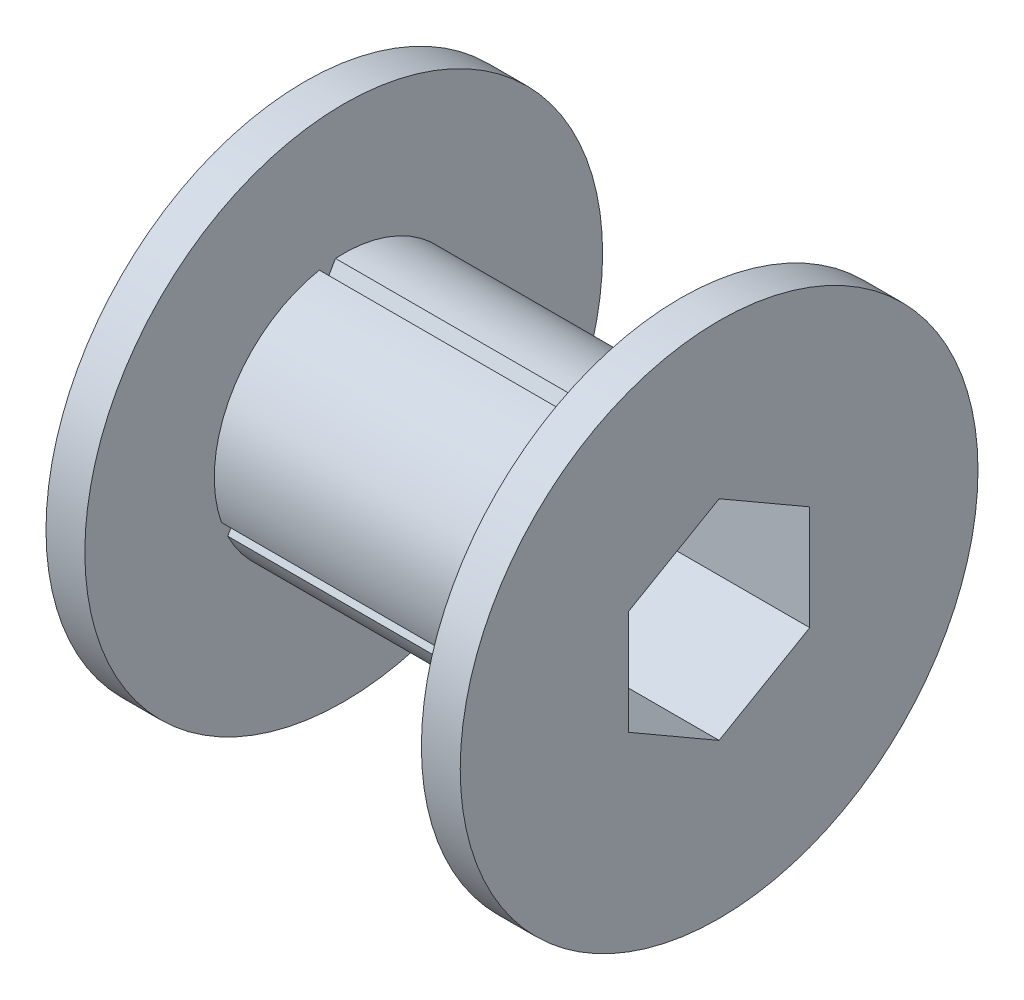
SolidWorks part; units mm, degrees
ref_plane "Front Plane" through (0, 0, 0) normal (0, 0, 1) x (1, 0, 0)
ref_plane "Top Plane" through (0, 0, 0) normal (0, 1, 0) x (1, 0, 0)
ref_plane "Right Plane" through (0, 0, 0) normal (1, 0, 0) x (0, 0, -1)
sketch "Sketch1" plane through (0, 0, 0) normal (1, 0, 0) x (0, 0, -1)
  circle A0 centre (0, 0) radius 2.5
  dimension "D1" = 5
extrude "Boss-Extrude1" add sketch "Sketch1" along normal mid plane 8
sketch "Sketch2" plane through (4, 0, 0) normal (1, 0, 0) x (0, 0, -1)
  circle A0 centre (0, 0) radius 5
  dimension "D1" = 10
extrude "Boss-Extrude2" add sketch "Sketch2" against normal blind 0.75
mirror "Mirror1" about plane through (0, 0, 0) normal (1, 0, 0) of "Boss-Extrude2"
sketch "Sketch3" plane through (0, 0, 0) normal (1, 0, 0) x (0, 0, -1)
  line L0 (1.75, 0) -> (1.75, 1.0104)
  line L1 (1.6, 0) -> (1.6, 0.9238) construction
  line L2 (1.6, -0.9238) -> (1.6, 0) construction
  line L3 (0.8, -1.3856) -> (1.6, -0.9238) construction
  line L4 (0, -1.8475) -> (0.8, -1.3856) construction
  line L5 (-0.8, -1.3856) -> (0, -1.8475) construction
  line L6 (-1.6, -0.9238) -> (-0.8, -1.3856) construction
  line L7 (-1.6, 0) -> (-1.6, -0.9238) construction
  line L8 (-1.6, 0.9238) -> (-1.6, 0) construction
  line L9 (-0.8, 1.3856) -> (-1.6, 0.9238) construction
  line L10 (0, 1.8475) -> (-0.8, 1.3856) construction
  line L11 (0.8, 1.3856) -> (0, 1.8475) construction
  line L12 (1.6, 0.9238) -> (0.8, 1.3856) construction
  line L13 (1.6, 0) -> (1.6, 0.9238) construction
  line L14 (1.6, -0.9238) -> (1.6, 0) construction
  line L15 (0.8, -1.3856) -> (1.6, -0.9238) construction
  line L16 (0, -1.8475) -> (0.8, -1.3856) construction
  line L17 (-0.8, -1.3856) -> (0, -1.8475) construction
  line L18 (-1.6, -0.9238) -> (-0.8, -1.3856) construction
  line L19 (-1.6, 0) -> (-1.6, -0.9238) construction
  line L20 (-1.6, 0.9238) -> (-1.6, 0) construction
  line L21 (-0.8, 1.3856) -> (-1.6, 0.9238) construction
  line L22 (0, 1.8475) -> (-0.8, 1.3856) construction
  line L23 (0.8, 1.3856) -> (0, 1.8475) construction
  line L24 (1.6, 0.9238) -> (0.8, 1.3856) construction
  line L25 (1.75, 1.0104) -> (0.875, 1.5155)
  line L26 (0.875, 1.5155) -> (0, 2.0207)
  line L27 (0, 2.0207) -> (-0.875, 1.5155)
  line L28 (-0.875, 1.5155) -> (-1.75, 1.0104)
  line L29 (-1.75, 1.0104) -> (-1.75, 0)
  line L30 (-1.75, 0) -> (-1.75, -1.0104)
  line L31 (-1.75, -1.0104) -> (-0.875, -1.5155)
  line L32 (-0.875, -1.5155) -> (0, -2.0207)
  line L33 (0, -2.0207) -> (0.875, -1.5155)
  line L34 (0.875, -1.5155) -> (1.75, -1.0104)
  line L35 (1.75, -1.0104) -> (1.75, 0)
  dimension "D1" = 0.15
extrude "M1.6 Nut" cut sketch "Sketch3" against normal through all both and the other way through all
sketch "Sketch5" plane through (0, 1.0104, -1.75) normal (0, -0.866, 0.5) x (1, 0, 0)
  line L0 (3.25, 3.5104) -> (3.25, -1.4896) construction
  line L1 (3.25, 2.6457) -> (-3.25, 2.6457)
  line L2 (3.25, 2.6457) -> (3.25, 2.3957)
  line L3 (3.25, 2.3957) -> (-3.25, 2.3957)
  line L4 (-4, 2.0207) -> (4, 2.0207) construction
  line L12 (-3.25, 2.6457) -> (-3.25, 2.3957)
  line L13 (3.25, 2.6457) -> (-3.25, 2.3957) construction
  line L14 (3.25, 2.3957) -> (-3.25, 2.6457) construction
  point P0 (0, 0)
  point P2 (0, 2.5207)
  dimension "D2" = 0.5
  dimension "D1" = 0.25
extrude "Cut-Extrude1" cut sketch "Sketch5" along normal through all both and the other way through all
